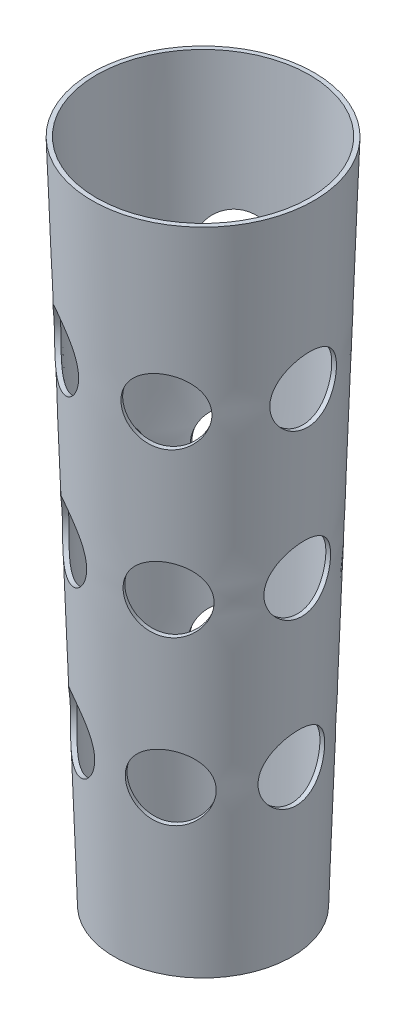
SolidWorks part; units mm, degrees
ref_plane "Спереди" through (0, 0, 0) normal (0, 0, 1) x (1, 0, 0)
ref_plane "Сверху" through (0, 0, 0) normal (0, 1, 0) x (1, 0, 0)
ref_plane "Справа" through (0, 0, 0) normal (1, 0, 0) x (0, 0, -1)
sketch "Эскиз1" plane through (0, 0, 0) normal (0, 0, 1) x (1, 0, 0)
  line L0 (0, 0) -> (0, 15) construction
  line L1 (0, 0) -> (-2, 0)
  line L2 (-2, 0) -> (-2.5, 15)
  line L3 (-2.5, 15) -> (0, 15) construction
  point P8 (0, 7.5)
  dimension "D1" = 5
  dimension "D2" = 15
  dimension "D3" = 0.5
revolve "Повернуть-Тонкостенный1" add sketch "Эскиз1" angle 360 about L0
sketch "Эскиз2" plane through (0, 0, 0) normal (1, 0, 0) x (0, 0, -1)
  line L0 (0, 0) -> (0, 3.7508) construction
  line L3 (-2, 0) -> (2, 0) construction
  line L4 (0, 11.2525) -> (0, 15.0033) construction
  line L5 (2.4001, 15.0033) -> (-2.4001, 15.0033) construction
  line L6 (0, 3.7508) -> (0, 7.5017) construction
  circle A0 centre (0, 3.7508) radius 0.75
  circle A1 centre (0, 7.5017) radius 0.75
  circle A2 centre (0, 11.2525) radius 0.75
  point P7 (0, 7.5017)
  point P13 (0, 11.2525)
  dimension "D2" = 1.5
  dimension "D1" = 3
extrude "Вырез-Вытянуть1" cut sketch "Эскиз2" against normal mid plane 10
pattern_circular "Круговой массив1" count 3 over 360 about axis through (0, 15, 0) along (0, -1, 0) of "Вырез-Вытянуть1"
